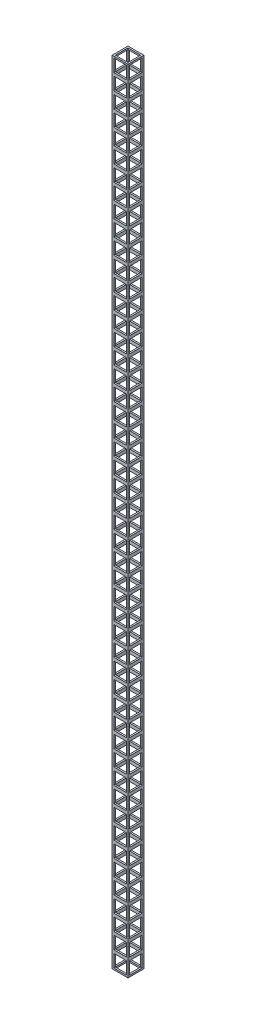
SolidWorks part; units mm, degrees
ref_plane "Ebene vorne" through (0, 0, 0) normal (0, 0, 1) x (1, 0, 0)
ref_plane "Ebene oben" through (0, 0, 0) normal (0, 1, 0) x (1, 0, 0)
ref_plane "Ebene rechts" through (0, 0, 0) normal (1, 0, 0) x (0, 0, -1)
sketch "Skizze1" plane through (0, 0, 0) normal (0, 0, 1) x (1, 0, 0)
  line L1 (0, 0) -> (50, 0)
  line L2 (0, 0) -> (0, 2500)
  line L3 (0, 2500) -> (50, 2500)
  line L4 (50, 0) -> (50, 2500)
  dimension "D1" = 2500
  dimension "D2" = 50
extrude "Aufsatz-Linear austragen1" add sketch "Skizze1" along normal blind 50
sketch "Skizze2" plane through (0, 2500, 0) normal (0, 1, 0) x (1, 0, 0)
  line L0 (50, 0) -> (0, 0) construction
  line L1 (5, -5) -> (45, -5)
  line L2 (5, -5) -> (5, -45)
  line L3 (5, -45) -> (45, -45)
  line L4 (45, -5) -> (45, -45)
  line L5 (50, -50) -> (0, -50) construction
  line L6 (0, -50) -> (0, 0) construction
  line L7 (50, -50) -> (50, 0) construction
  dimension "D1" = 5
  dimension "D2" = 5
  dimension "D3" = 5
  dimension "D4" = 5
extrude "Schnitt-Linear austragen1" cut sketch "Skizze2" against normal through all
sketch "Skizze3" plane through (0, 0, 50) normal (0, 0, 1) x (1, 0, 0)
  line L0 (0, 2500) -> (0, 0) construction
  line L1 (5, 2495) -> (45, 2495)
  line L2 (5, 2495) -> (5, 2455)
  line L3 (5, 2455) -> (45, 2455)
  line L4 (45, 2495) -> (45, 2455)
  line L5 (50, 2500) -> (0, 2500) construction
  line L6 (50, 0) -> (50, 2500) construction
  dimension "D1" = 5
  dimension "D2" = 5
  dimension "D3" = 5
  dimension "D4" = 40
extrude "Schnitt-Linear austragen2" cut sketch "Skizze3" against normal through all both and the other way through all
sketch "Skizze4" plane through (50, 0, 0) normal (1, 0, 0) x (0, 0, -1)
  line L0 (-50, 2500) -> (0, 2500) construction
  line L1 (-45, 2495) -> (-5, 2495)
  line L2 (-45, 2495) -> (-45, 2455)
  line L3 (-45, 2455) -> (-5, 2455)
  line L4 (-5, 2495) -> (-5, 2455)
  line L5 (-50, 0) -> (-50, 2500) construction
  line L6 (0, 0) -> (0, 2500) construction
  dimension "D1" = 40
  dimension "D2" = 5
  dimension "D3" = 5
  dimension "D4" = 5
extrude "Schnitt-Linear austragen3" cut sketch "Skizze4" against normal through all both and the other way through all
pattern_linear "Lineares Muster1" count 50 spacing 50 along (0, -1, 0) of "Schnitt-Linear austragen2"
pattern_linear "Lineares Muster2" count 50 spacing 50 along (0, -1, 0) of "Schnitt-Linear austragen3"
